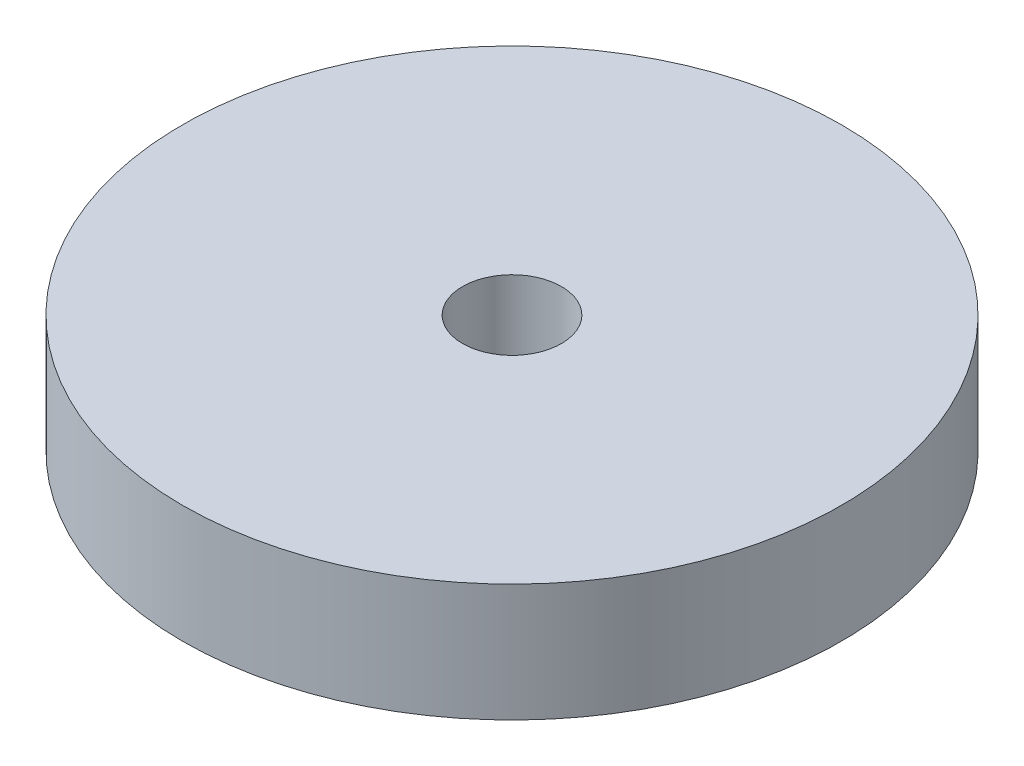
SolidWorks part; units mm, degrees
ref_plane "Front Plane" through (0, 0, 0) normal (0, 0, 1) x (1, 0, 0)
ref_plane "Top Plane" through (0, 0, 0) normal (0, 1, 0) x (1, 0, 0)
ref_plane "Right Plane" through (0, 0, 0) normal (1, 0, 0) x (0, 0, -1)
sketch "Sketch1" plane through (0, 0, 0) normal (0, 1, 0) x (1, 0, 0)
  circle A0 centre (0, 0) radius 14
  circle A1 centre (0, 0) radius 2.1
  dimension "D1" = 28
  dimension "D2" = 4.2
extrude "Boss-Extrude1" add sketch "Sketch1" along normal mid plane 5
ref_plane "Plane1" through (30, 0, 0) normal (1, 0, 0) x (0, 0, -1)
